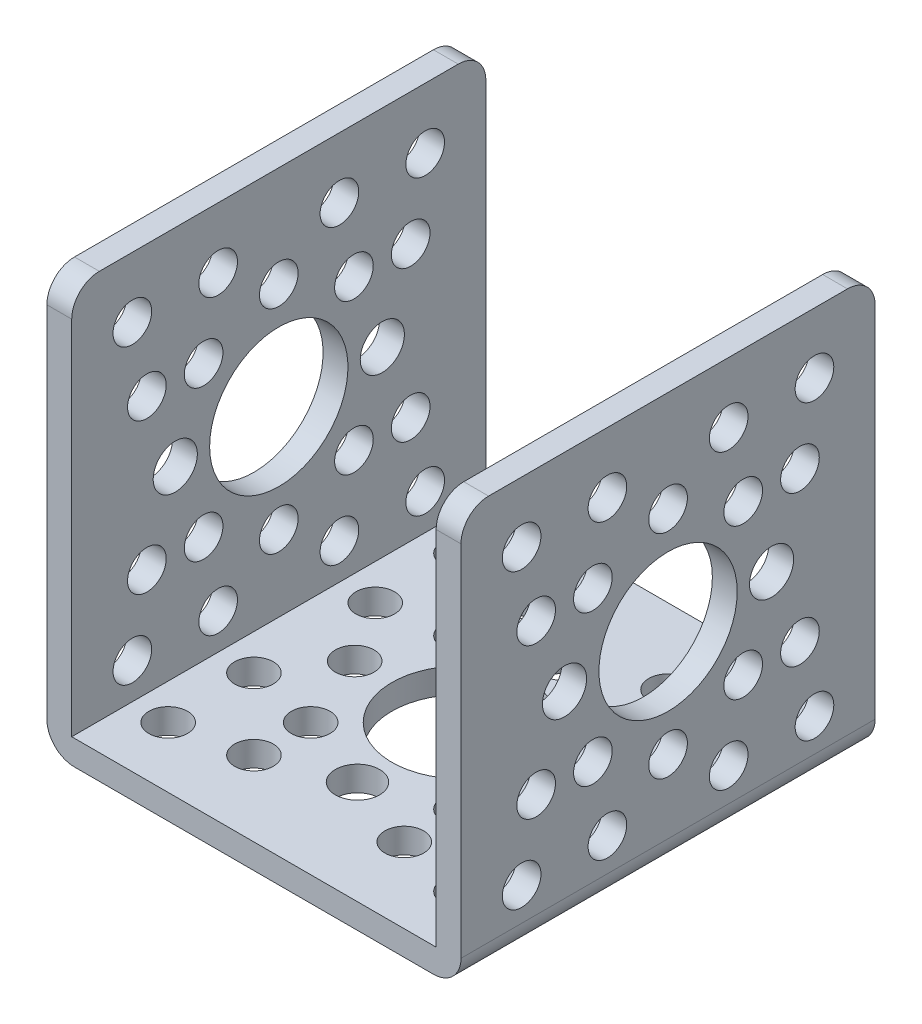
SolidWorks part; units mm, degrees
ref_plane "Front Plane" through (0, 0, 0) normal (0, 0, 1) x (1, 0, 0)
ref_plane "Top Plane" through (0, 0, 0) normal (0, 1, 0) x (1, 0, 0)
ref_plane "Right Plane" through (0, 0, 0) normal (1, 0, 0) x (0, 0, -1)
ref_plane "Plane1" through (38.1, 0, 0) normal (1, 0, 0) x (0, 0, -1)
sketch "Sketch1" plane through (38.1, 0, 0) normal (1, 0, 0) x (0, 0, -1)
  line L0 (0, 38.1) -> (-38.1, 38.1)
  line L1 (-38.1, 38.1) -> (-38.1, 0)
  line L2 (-38.1, 0) -> (0, 0)
  line L3 (0, 0) -> (0, 38.1)
extrude "Boss-Extrude1" add sketch "Sketch1" against normal blind 38.1
sketch "Sketch2" plane through (0, 0, 38.1) normal (0, 0, 1) x (1, 0, 0)
  line L0 (35.814, 38.1) -> (2.286, 38.1)
  line L1 (2.286, 38.1) -> (2.286, 2.286)
  line L2 (2.286, 2.286) -> (35.814, 2.286)
  line L3 (35.814, 2.286) -> (35.814, 38.1)
extrude "Cut-Extrude1" cut sketch "Sketch2" against normal through all
hole_wizard "Hole1" positions "Sketch4" profile "Sketch3" legacy
sketch "Sketch4" plane through (0, 0, 0) normal (-1, 0, 0) x (0, 0, 1)
  point P0 (19.05, 19.05)
sketch "Sketch3" plane through (0, 19.05, 19.05) normal (0, 1, 0) x (0, 0, 1)
  line L0 (0, 0) -> (0, 2.286)
  line L1 (0, 2.286) -> (6.3627, 2.286)
  line L2 (6.3627, 2.286) -> (6.3627, 0)
  line L3 (6.3627, 0) -> (0, 0)
  line L4 (0, 110) -> (0, -10) construction
  dimension "Diameter" = 12.7254
  dimension "Depth" = 2.286
hole_wizard "#6 Clearance Hole1" positions "Sketch6" profile "Sketch5" hole size "#6" standard "ANSI Inch"
sketch "Sketch6" plane through (0, 0, 0) normal (-1, 0, 0) x (0, 0, 1)
  point P0 (28.575, 19.05)
  point P1 (9.525, 19.05)
sketch "Sketch5" plane through (0, 19.05, 28.575) normal (0, 1, 0) x (0, 0, 1)
  line L0 (0, 0) -> (0, 2.286)
  line L1 (0, 2.286) -> (2.032, 2.286)
  line L2 (2.032, 2.286) -> (2.032, 0)
  line L5 (2.032, 0) -> (0, 0)
  line L11 (0, -6.35) -> (0, 107.95) construction
  dimension "Thru Hole Dia." = 4.064
  dimension "Thru Hole Depth" = 2.286
hole_wizard "#5 Clearance Hole1" positions "Sketch8" profile "Sketch7" hole size "#5" standard "ANSI Inch"
sketch "Sketch8" plane through (0, 0, 0) normal (-1, 0, 0) x (0, 0, 1)
  point P0 (24.6296, 5.5796)
  point P1 (31.1852, 12.1352)
  point P2 (24.6296, 32.5204)
  point P3 (31.1852, 25.9648)
  point P4 (13.4704, 5.5796)
  point P5 (6.9148, 12.1352)
  point P6 (13.4704, 32.5204)
  point P7 (6.9148, 25.9648)
  point P8 (32.5204, 5.5796)
  point P9 (32.5204, 32.5204)
  point P10 (5.5796, 5.5796)
  point P11 (5.5796, 32.5204)
  point P12 (12.1352, 12.1352)
  point P13 (19.05, 9.271)
  point P14 (25.9648, 12.1352)
  point P15 (25.9648, 25.9648)
  point P16 (19.05, 28.829)
  point P17 (12.1352, 25.9648)
sketch "Sketch7" plane through (0, 5.5796, 24.6296) normal (0, 1, 0) x (0, 0, 1)
  line L0 (0, 0) -> (0, 2.286)
  line L1 (0, 2.286) -> (1.778, 2.286)
  line L2 (1.778, 2.286) -> (1.778, 0)
  line L5 (1.778, 0) -> (0, 0)
  line L11 (0, -6.35) -> (0, 107.95) construction
  dimension "Thru Hole Dia." = 3.556
  dimension "Thru Hole Depth" = 2.286
hole_wizard "Hole2" positions "Sketch10" profile "Sketch9" legacy
sketch "Sketch10" plane through (0, 0, 0) normal (0, -1, 0) x (-1, 0, 0)
  point P0 (-19.05, -19.05)
sketch "Sketch9" plane through (19.05, 0, 19.05) normal (1, 0, 0) x (0, 0, -1)
  line L0 (0, 0) -> (0, 38.1)
  line L1 (0, 38.1) -> (6.3627, 38.1)
  line L2 (6.3627, 38.1) -> (6.3627, 0)
  line L3 (6.3627, 0) -> (0, 0)
  line L4 (0, 110) -> (0, -10) construction
  dimension "Diameter" = 12.7254
  dimension "Depth" = 38.1
hole_wizard "#6 Clearance Hole2" positions "Sketch12" profile "Sketch11" hole size "#6" standard "ANSI Inch"
sketch "Sketch12" plane through (0, 0, 0) normal (0, -1, 0) x (-1, 0, 0)
  point P0 (-19.05, -28.575)
  point P1 (-19.05, -9.525)
sketch "Sketch11" plane through (19.05, 0, 28.575) normal (1, 0, 0) x (0, 0, -1)
  line L0 (0, 0) -> (0, 38.1)
  line L1 (0, 38.1) -> (2.032, 38.1)
  line L2 (2.032, 38.1) -> (2.032, 0)
  line L5 (2.032, 0) -> (0, 0)
  line L11 (0, -6.35) -> (0, 107.95) construction
  dimension "Thru Hole Dia." = 4.064
  dimension "Thru Hole Depth" = 38.1
hole_wizard "#5 Clearance Hole2" positions "Sketch14" profile "Sketch13" hole size "#5" standard "ANSI Inch"
sketch "Sketch14" plane through (0, 0, 0) normal (0, -1, 0) x (-1, 0, 0)
  point P0 (-5.5796, -32.5204)
  point P1 (-5.5796, -24.6296)
  point P2 (-12.1352, -31.1852)
  point P3 (-32.5204, -32.5204)
  point P4 (-32.5204, -24.6296)
  point P5 (-25.9648, -31.1852)
  point P6 (-5.5796, -5.5796)
  point P7 (-5.5796, -13.4704)
  point P8 (-12.1352, -6.9148)
  point P9 (-32.5204, -5.5796)
  point P10 (-32.5204, -13.4704)
  point P11 (-25.9648, -6.9148)
  point P12 (-12.1352, -12.1352)
  point P13 (-9.271, -19.05)
  point P14 (-12.1352, -25.9648)
  point P15 (-25.9648, -25.9648)
  point P16 (-28.829, -19.05)
  point P17 (-25.9648, -12.1352)
sketch "Sketch13" plane through (5.5796, 0, 32.5204) normal (1, 0, 0) x (0, 0, -1)
  line L0 (0, 0) -> (0, 38.1)
  line L1 (0, 38.1) -> (1.778, 38.1)
  line L2 (1.778, 38.1) -> (1.778, 0)
  line L5 (1.778, 0) -> (0, 0)
  line L11 (0, -6.35) -> (0, 107.95) construction
  dimension "Thru Hole Dia." = 3.556
  dimension "Thru Hole Depth" = 38.1
hole_wizard "Hole3" positions "Sketch16" profile "Sketch15" legacy
sketch "Sketch16" plane through (38.1, 0, 0) normal (1, 0, 0) x (0, 0, -1)
  point P0 (-19.05, 19.05)
sketch "Sketch15" plane through (38.1, 19.05, 19.05) normal (0, 1, 0) x (0, 0, -1)
  line L0 (0, 0) -> (0, 38.1)
  line L1 (0, 38.1) -> (6.3627, 38.1)
  line L2 (6.3627, 38.1) -> (6.3627, 0)
  line L3 (6.3627, 0) -> (0, 0)
  line L4 (0, 110) -> (0, -10) construction
  dimension "Diameter" = 12.7254
  dimension "Depth" = 38.1
hole_wizard "#6 Clearance Hole3" positions "Sketch18" profile "Sketch17" hole size "#6" standard "ANSI Inch"
sketch "Sketch18" plane through (38.1, 0, 0) normal (1, 0, 0) x (0, 0, -1)
  point P0 (-28.575, 19.05)
  point P1 (-9.525, 19.05)
sketch "Sketch17" plane through (38.1, 19.05, 28.575) normal (0, 1, 0) x (0, 0, -1)
  line L0 (0, 0) -> (0, 38.1)
  line L1 (0, 38.1) -> (2.032, 38.1)
  line L2 (2.032, 38.1) -> (2.032, 0)
  line L5 (2.032, 0) -> (0, 0)
  line L11 (0, -6.35) -> (0, 107.95) construction
  dimension "Thru Hole Dia." = 4.064
  dimension "Thru Hole Depth" = 38.1
hole_wizard "#5 Clearance Hole3" positions "Sketch20" profile "Sketch19" hole size "#5" standard "ANSI Inch"
sketch "Sketch20" plane through (38.1, 0, 0) normal (1, 0, 0) x (0, 0, -1)
  point P0 (-31.1852, 12.1352)
  point P1 (-31.1852, 25.9648)
  point P2 (-6.9148, 12.1352)
  point P3 (-13.4704, 32.5204)
  point P4 (-6.9148, 25.9648)
  point P5 (-32.5204, 5.5796)
  point P6 (-32.5204, 32.5204)
  point P7 (-5.5796, 5.5796)
  point P8 (-5.5796, 32.5204)
  point P9 (-12.1352, 12.1352)
  point P10 (-19.05, 9.271)
  point P11 (-25.9648, 12.1352)
  point P12 (-25.9648, 25.9648)
  point P13 (-19.05, 28.829)
  point P14 (-12.1352, 25.9648)
  point P15 (-13.4704, 5.5796)
  point P16 (-24.6296, 32.5204)
  point P17 (-24.6296, 5.5796)
sketch "Sketch19" plane through (38.1, 12.1352, 31.1852) normal (0, 1, 0) x (0, 0, -1)
  line L0 (0, 0) -> (0, 38.1)
  line L1 (0, 38.1) -> (1.778, 38.1)
  line L2 (1.778, 38.1) -> (1.778, 0)
  line L5 (1.778, 0) -> (0, 0)
  line L11 (0, -6.35) -> (0, 107.95) construction
  dimension "Thru Hole Dia." = 3.556
  dimension "Thru Hole Depth" = 38.1
fillet "Fillet1" radius 2.54 6 edges at (0, 0, 19.05) (1.143, 38.1, 38.1) (1.143, 38.1, 0) (36.957, 38.1, 38.1) (36.957, 38.1, 0) (38.1, 0, 19.05)
